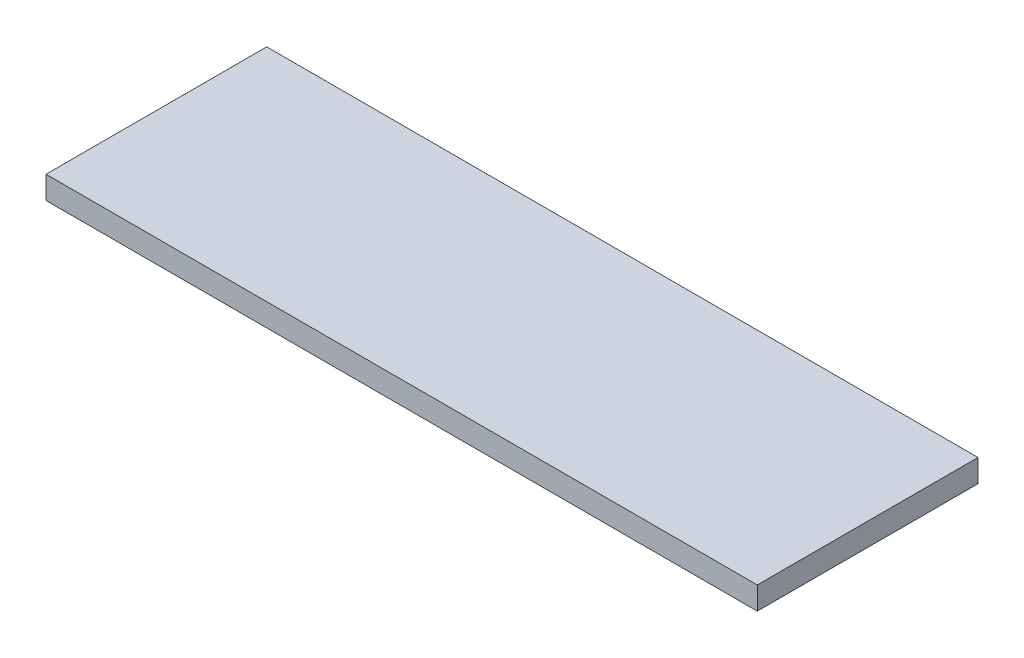
SolidWorks part; units mm, degrees
material "Sosna"
ref_plane "Płaszczyzna przednia" through (0, 0, 0) normal (0, 0, 1) x (1, 0, 0)
ref_plane "Płaszczyzna górna" through (0, 0, 0) normal (0, 1, 0) x (1, 0, 0)
ref_plane "Płaszczyzna prawa" through (0, 0, 0) normal (1, 0, 0) x (0, 0, -1)
sketch "Szkic1" plane through (0, 0, 0) normal (0, 1, 0) x (1, 0, 0)
  line L1 (0, 0) -> (-564, 0)
  line L2 (0, 0) -> (0, 175)
  line L3 (0, 175) -> (-564, 175)
  line L4 (-564, 0) -> (-564, 175)
  dimension "D1" = 564
  dimension "D2" = 175
extrude "Dodanie-wyciągnięcie1" add sketch "Szkic1" along normal blind 18
